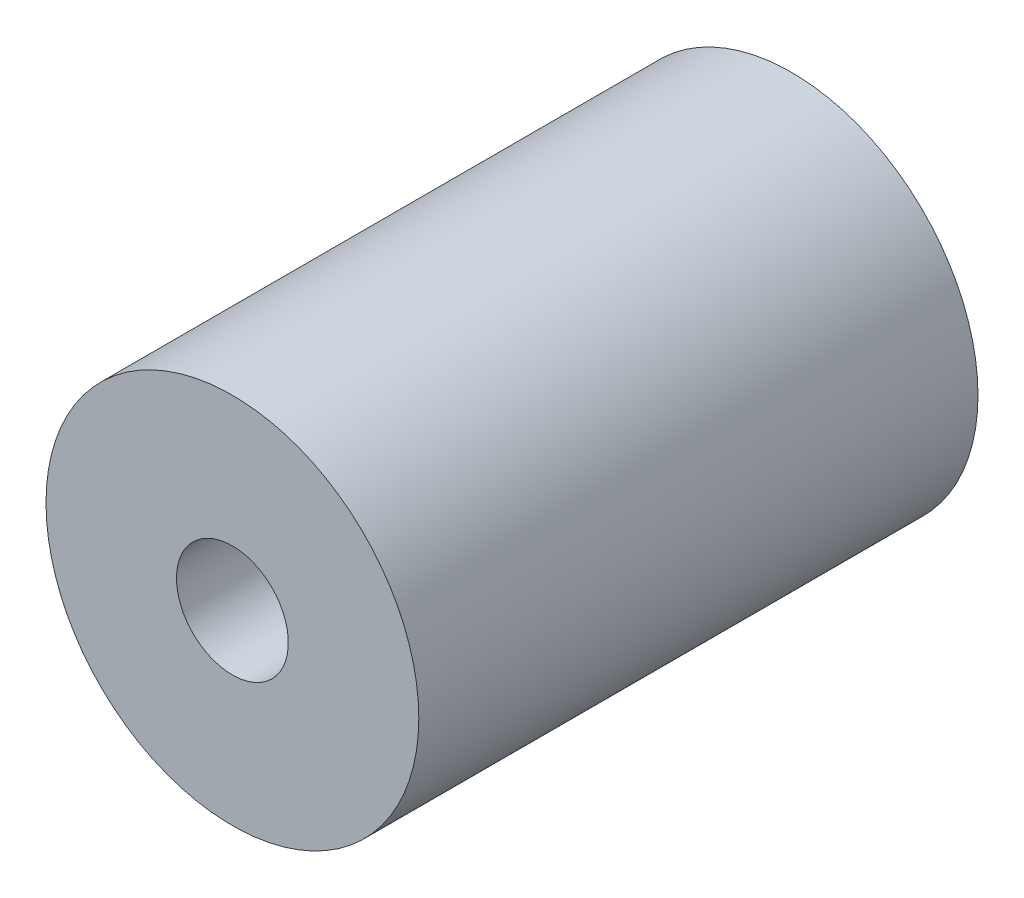
SolidWorks part; units mm, degrees
material "ABS"
ref_plane "Alzado" through (0, 0, 0) normal (0, 0, 1) x (1, 0, 0)
ref_plane "Planta" through (0, 0, 0) normal (0, 1, 0) x (1, 0, 0)
ref_plane "Vista lateral" through (0, 0, 0) normal (1, 0, 0) x (0, 0, -1)
sketch "Sketch1" plane through (0, 0, 0) normal (0, 1, 0) x (1, 0, 0)
  line L0 (0, 0) -> (5, 0)
  line L1 (5, 0) -> (5, 15)
  line L2 (5, 15) -> (0, 15)
  line L3 (0, 15) -> (0, 0)
  dimension "D1" = 5
  dimension "D2" = 15
revolve "Revolve1" add sketch "Sketch1" angle 360 about L3
hole_wizard "Ø3.0mm Dowel Hole1" positions "Sketch2" profile "Sketch3" hole size "Ø3.0" standard "ANSI Metric" end condition up to next
sketch "Sketch2" plane through (0, 0, -15) normal (0, 0, -1) x (-1, 0, 0)
  point P0 (0, 0)
sketch "Sketch3" plane through (0, 0, -15) normal (1, 0, 0) x (0, 1, 0)
  line L0 (0, 0) -> (0, 15)
  line L1 (0, 15) -> (1.5, 15)
  line L2 (1.5, 15) -> (1.5, 0)
  line L5 (1.5, 0) -> (0, 0)
  line L11 (0, -6.35) -> (0, 107.95) construction
  dimension "Thru Hole Dia." = 3
  dimension "Thru Hole Depth" = 15
equation "\"Altura_soporte\"= \"D2@Sketch1\"'d"
equation "\"diametro_soporte\"= \"D1@Sketch1\""
equation "\"D1@Sketch1\"=.50"
equation "\"D2@Sketch1\"=1.5"
